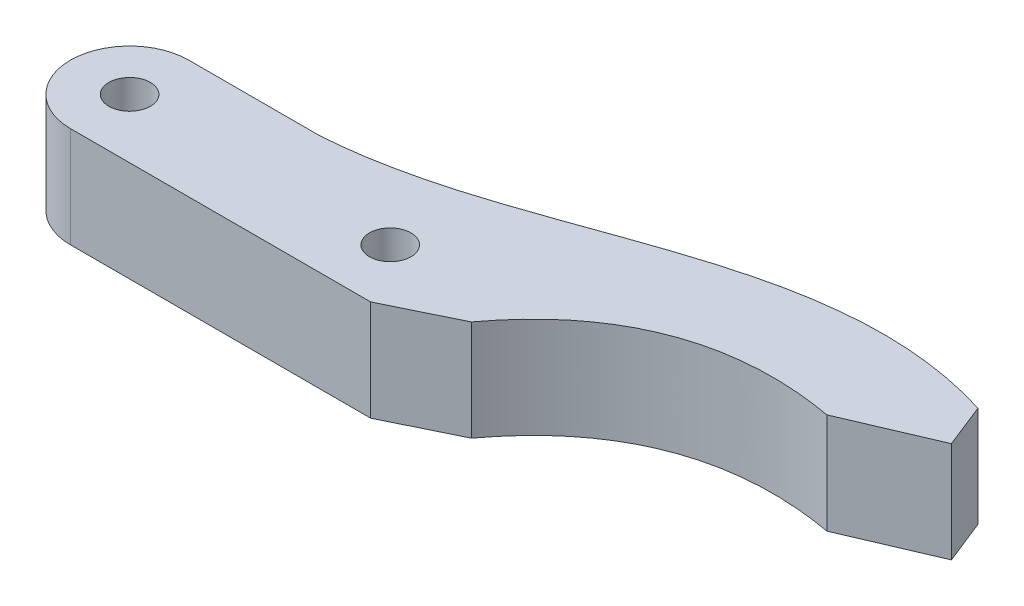
SolidWorks part; units mm, degrees
ref_plane "Front Plane" through (0, 0, 0) normal (0, 0, 1) x (1, 0, 0)
ref_plane "Top Plane" through (0, 0, 0) normal (0, 1, 0) x (1, 0, 0)
ref_plane "Right Plane" through (0, 0, 0) normal (1, 0, 0) x (0, 0, -1)
sketch "Sketch1" plane through (0, 0, 0) normal (0, 1, 0) x (1, 0, 0)
  line L0 (0, 0) -> (22, 0) construction
  line L1 (0, 5) -> (22, 5)
  line L3 (0, -5) -> (22, -5)
  line L5 (-2.6225, 4.257) -> (27, -5) construction
  line L6 (-5, -5) -> (24.6225, 4.257) construction
  circle A0 centre (0, 0) radius 1.75
  circle A1 centre (0, 0) radius 5
  circle A2 centre (22, 0) radius 1.75
  circle A3 centre (22, 0) radius 5
  arc A4 (22, 5) -> (22, -5) centre (22, 0) ccw
  arc A5 (0, 5) -> (0, -5) centre (0, 0) cw
  point P8 (11, 0)
  dimension "D2" = 10
  dimension "D3" = 3.5
  dimension "D1" = 22
extrude "Boss-Extrude2" add sketch "Sketch1" along normal blind 8.5 contours A5 L3 A4 L1 | A1 | A0 | A3 | A2
sketch "Sketch2" plane through (0, 8.5, 0) normal (0, 1, 0) x (1, 0, 0)
  line L0 (22, -5) -> (25.3464, -5)
  line L1 (25.3464, -5) -> (31.0618, -2.2124)
  line L2 (0, 5) -> (22, 5) construction
  line L3 (58.75, 12.87) -> (60.2225, 9.1509)
  line L4 (60.2225, 9.1509) -> (52.8691, 6)
  line L5 (0, -5) -> (22, -5) construction
  line L6 (11, 5) -> (22, 5)
  circle A0 centre (22, 0) radius 1.75 construction
  arc A1 (22, -5) -> (22, 5) centre (22, 0) ccw construction
  arc A2 (22, -5) -> (22, 5) centre (22, 0) ccw
  spline S0 degree 3 poles (11, 5) (27.5436, 6.0574) (40.7642, 18.4267) (58.75, 12.87) knots 0 0 0 0 1 1 1 1
  spline S1 degree 2 poles (31.0618, -2.2124) (38.9928, 8.5048) (52.8691, 6) knots 0 0 0 1 1 1
  point P16 (58.75, 8.87)
  point P17 (28.4407, 9.3501)
  point P18 (60.6469, 9.3501)
  point P19 (54.3433, 6)
  point P20 (31.1841, -1.6872)
  point P22 (58.75, 12.87)
  point P23 (60.2225, 9.3501)
  point P24 (38.3528, 4.2431)
  point P25 (31.0618, -2.2124)
  dimension "D6" = 36.75
  dimension "D1" = 4
  dimension "D2" = 8
  dimension "D3" = 17.87
  dimension "D4" = 11
  dimension "D5" = 26
  dimension "D7" = 25.3464
  dimension "D8" = 28.4407
  dimension "D9" = 31.0618
  dimension "D10" = 38.3528
  dimension "D11" = 52.8691
  dimension "D12" = 4.3501
  dimension "D13" = 0.7569
extrude "Boss-Extrude3" add sketch "Sketch2" against normal blind 8.5
